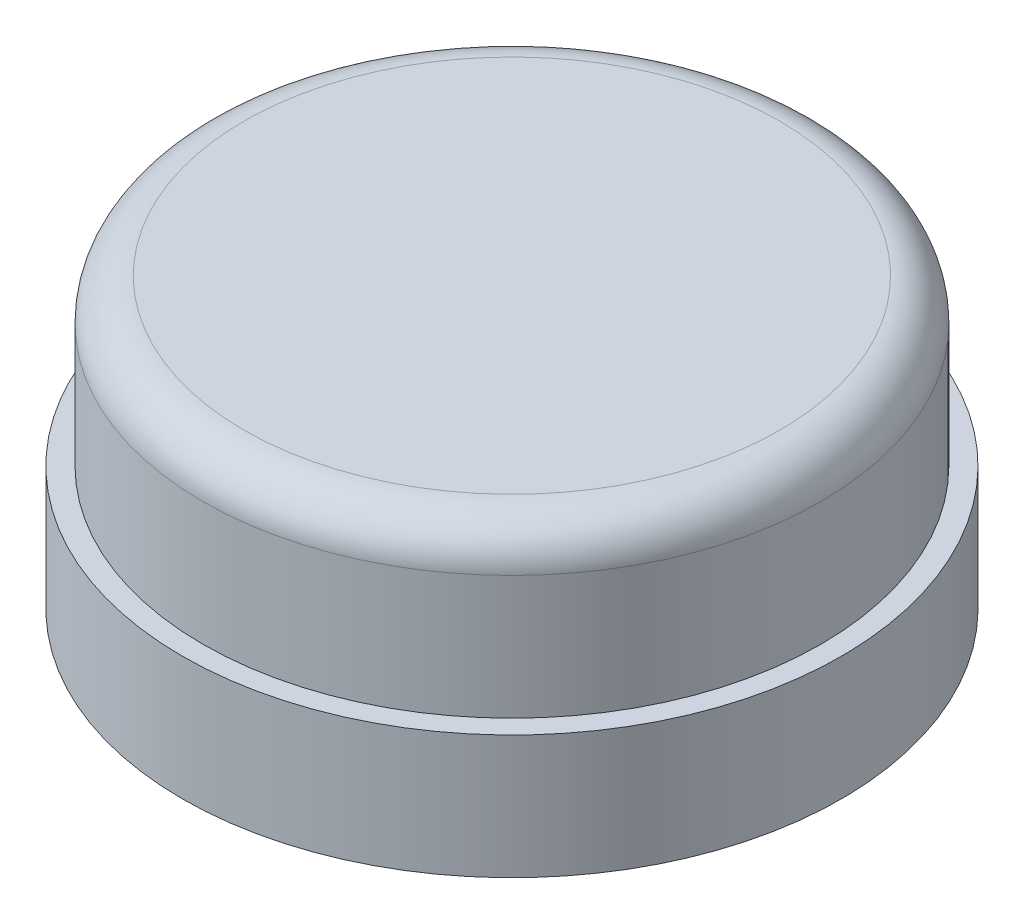
SolidWorks part; units mm, degrees
ref_plane "Front Plane" through (0, 0, 0) normal (0, 0, 1) x (1, 0, 0)
ref_plane "Top Plane" through (0, 0, 0) normal (0, 1, 0) x (1, 0, 0)
ref_plane "Right Plane" through (0, 0, 0) normal (1, 0, 0) x (0, 0, -1)
sketch "Sketch1" plane through (0, 0, 0) normal (0, 1, 0) x (1, 0, 0)
  circle A0 centre (0, 0) radius 8
  dimension "D1" = 16
extrude "Boss-Extrude1" add sketch "Sketch1" along normal blind 3
sketch "Sketch2" plane through (0, 3, 0) normal (0, 1, 0) x (1, 0, 0)
  circle A0 centre (0, 0) radius 7.5
  dimension "D1" = 15
extrude "Boss-Extrude2" add sketch "Sketch2" along normal blind 4
fillet "Fillet1" radius 1 1 edges at (0, 7, 7.5)
